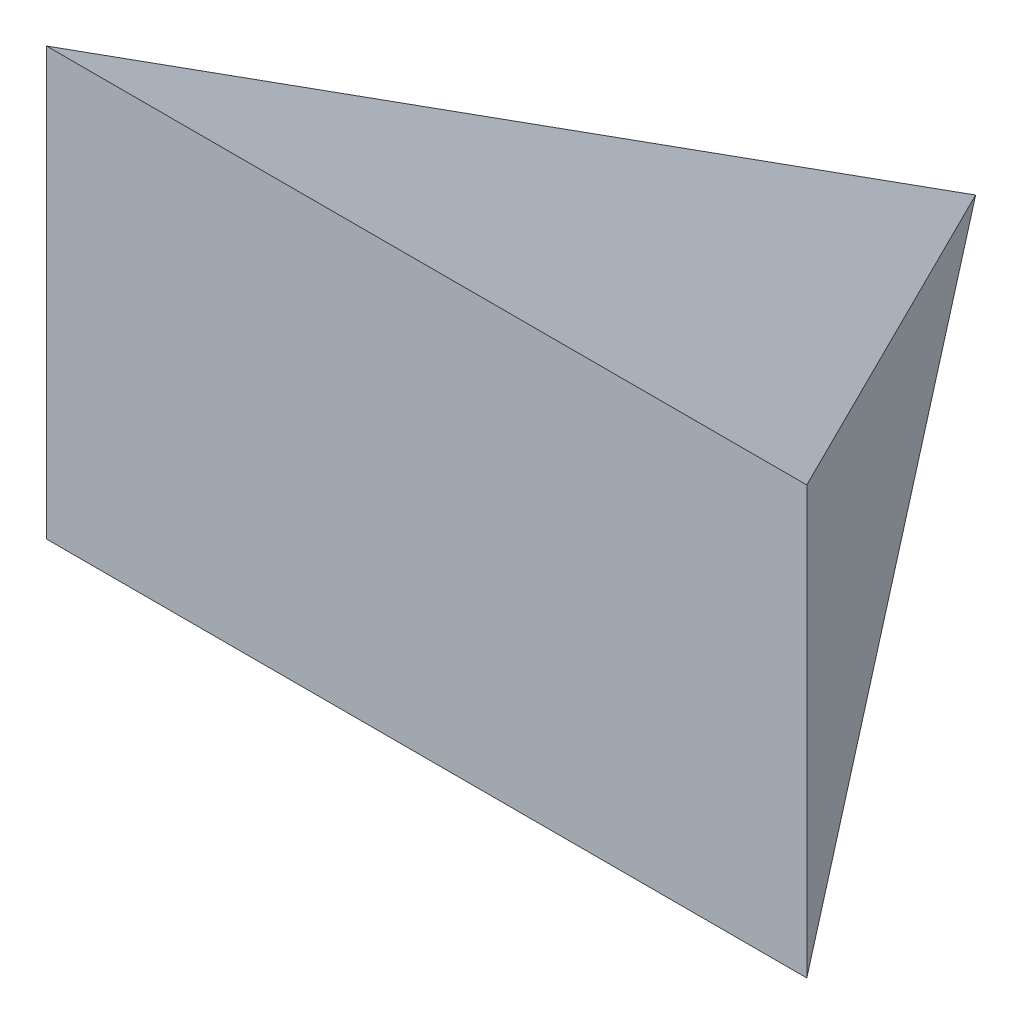
SolidWorks part; units mm, degrees
ref_plane "Front Plane" through (0, 0, 0) normal (0, 0, 1) x (1, 0, 0)
ref_plane "Top Plane" through (0, 0, 0) normal (0, 1, 0) x (1, 0, 0)
ref_plane "Right Plane" through (0, 0, 0) normal (1, 0, 0) x (0, 0, -1)
sketch "Sketch1" plane through (0, 0, -0.1) normal (0, 0, 1) x (1, 0, 0)
  line L1 (26.1, 3.6) -> (38.9, 3.6)
  line L2 (26.1, 3.6) -> (26.1, -3.6)
  line L3 (26.1, -3.6) -> (38.9, -3.6)
  line L4 (38.9, 3.6) -> (38.9, -3.6)
  line L5 (26.1, 3.6) -> (38.9, -3.6) construction
  line L6 (26.1, -3.6) -> (38.9, 3.6) construction
  circle A1 centre (32.5, 0) radius 3.3503 construction
  point P0 (32.5, 0)
  point P5 (0, 0)
  point P6 (33.3037, -2.0011)
  point P9 (0, 0)
  point P10 (0, 0)
  dimension "D1" = 7.2
  dimension "D2" = 12.8
extrude "Boss-Extrude1" add sketch "Sketch1" along normal blind 10000 draft 34.7
sketch "Sketch2" plane through (0, 0, 0) normal (1, 0, 0) x (0, 0, -1)
  line L0 (0.1, 3.6) -> (0.1, -3.6)
  line L1 (0.1, -3.6) -> (-58862.1051, -22893.8597)
  line L2 (-58862.1051, -22893.8597) -> (-798.7672, -29978.1232)
  line L3 (-798.7672, -29978.1232) -> (17319.323, 20158.8487)
  line L4 (17319.323, 20158.8487) -> (-60605.3988, 23571.7895)
  line L6 (0.1, 0) -> (-8.9521, 0) construction
  line L7 (0.1, 3.6) -> (-60605.3988, 23571.7895)
  dimension "D1" = 42.5
  dimension "D2" = 21.25
extrude "Cut-Extrude1" cut sketch "Sketch2" against normal through all both and the other way through all
equation "\"D2@Sketch2\"=\"D1@Sketch2\"/2"
